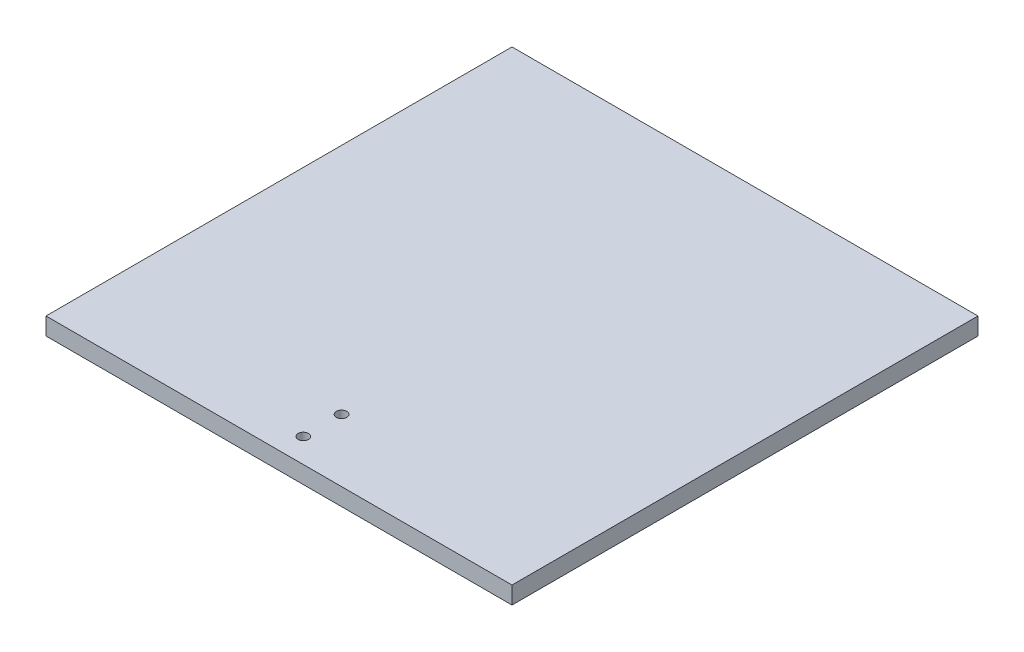
SolidWorks part; units mm, degrees
ref_plane "Plano frontal" through (0, 0, 0) normal (0, 0, 1) x (1, 0, 0)
ref_plane "Plano superior" through (0, 0, 0) normal (0, 1, 0) x (1, 0, 0)
ref_plane "Plano direito" through (0, 0, 0) normal (1, 0, 0) x (0, 0, -1)
sketch "Esboço1" plane through (0, 0, 0) normal (0, 1, 0) x (1, 0, 0)
  line L1 (-32.7468, 60.337) -> (101.3232, 60.337)
  line L2 (-32.7468, 60.337) -> (-32.7468, -73.733)
  line L3 (-32.7468, -73.733) -> (101.3232, -73.733)
  line L4 (101.3232, 60.337) -> (101.3232, -73.733)
extrude "Ressalto-extrusão1" add sketch "Esboço1" along normal blind 5
sketch "Esboço2" plane through (0, 5, 0) normal (0, 1, 0) x (1, 0, 0)
  line L0 (-32.7468, -73.733) -> (101.3232, -73.733) construction
  line L1 (-32.7468, 60.337) -> (-32.7468, -73.733) construction
  line L2 (101.3232, -73.733) -> (101.3232, 60.337) construction
  circle A0 centre (34.2882, -55.733) radius 1.5
  circle A1 centre (34.2882, -66.733) radius 1.5
  dimension "D1" = 7
  dimension "D2" = 11
  dimension "D3" = 67.035
  dimension "D4" = 67.035
extrude "Corte-extrusão1" cut sketch "Esboço2" against normal blind 5
